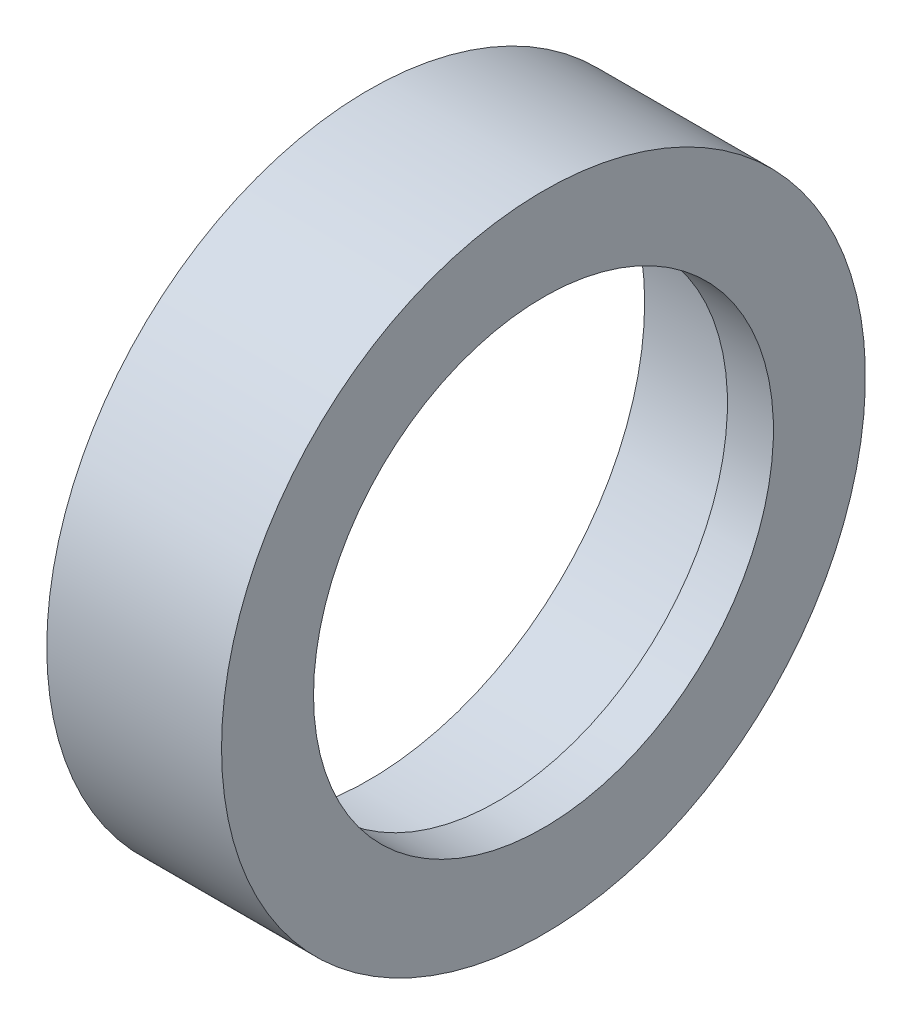
SolidWorks part; units mm, degrees
ref_plane "Front Plane" through (0, 0, 0) normal (0, 0, 1) x (1, 0, 0)
ref_plane "Top Plane" through (0, 0, 0) normal (0, 1, 0) x (1, 0, 0)
ref_plane "Right Plane" through (0, 0, 0) normal (1, 0, 0) x (0, 0, -1)
sketch "Sketch1" plane through (0, 0, 0) normal (0, 0, 1) x (1, 0, 0)
  line L6 (-15.3727, 0) -> (20.2025, 0) construction
  line L7 (-19, 35) -> (-19, 30)
  line L8 (0, 35) -> (-19, 35)
  line L9 (0, 25) -> (0, 35)
  line L10 (-5, 25) -> (0, 25)
  line L11 (-5, 30) -> (-5, 25)
  line L12 (-19, 30) -> (-5, 30)
  dimension "D1" = 5
  dimension "D2" = 19
  dimension "D3" = 5
  dimension "D4" = 10
  dimension "D5" = 50
revolve "Revolve1" add sketch "Sketch1" angle 360 about L6
